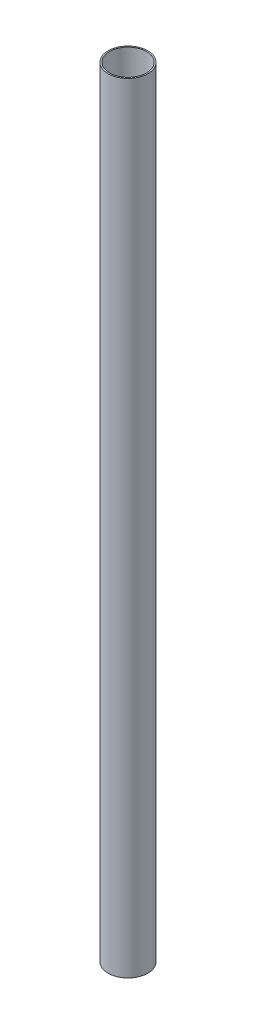
SolidWorks part; units mm, degrees
ref_plane "Front Plane" through (0, 0, 0) normal (0, 0, 1) x (1, 0, 0)
ref_plane "Top Plane" through (0, 0, 0) normal (0, 1, 0) x (1, 0, 0)
ref_plane "Right Plane" through (0, 0, 0) normal (1, 0, 0) x (0, 0, -1)
sketch "Sketch1" plane through (0, 0, 0) normal (0, 1, 0) x (1, 0, 0)
  circle A0 centre (0, 0) radius 5.1013
  circle A1 centre (0, 0) radius 4.7604
extrude "Boss-Extrude1" add sketch "Sketch1" along normal blind 200
